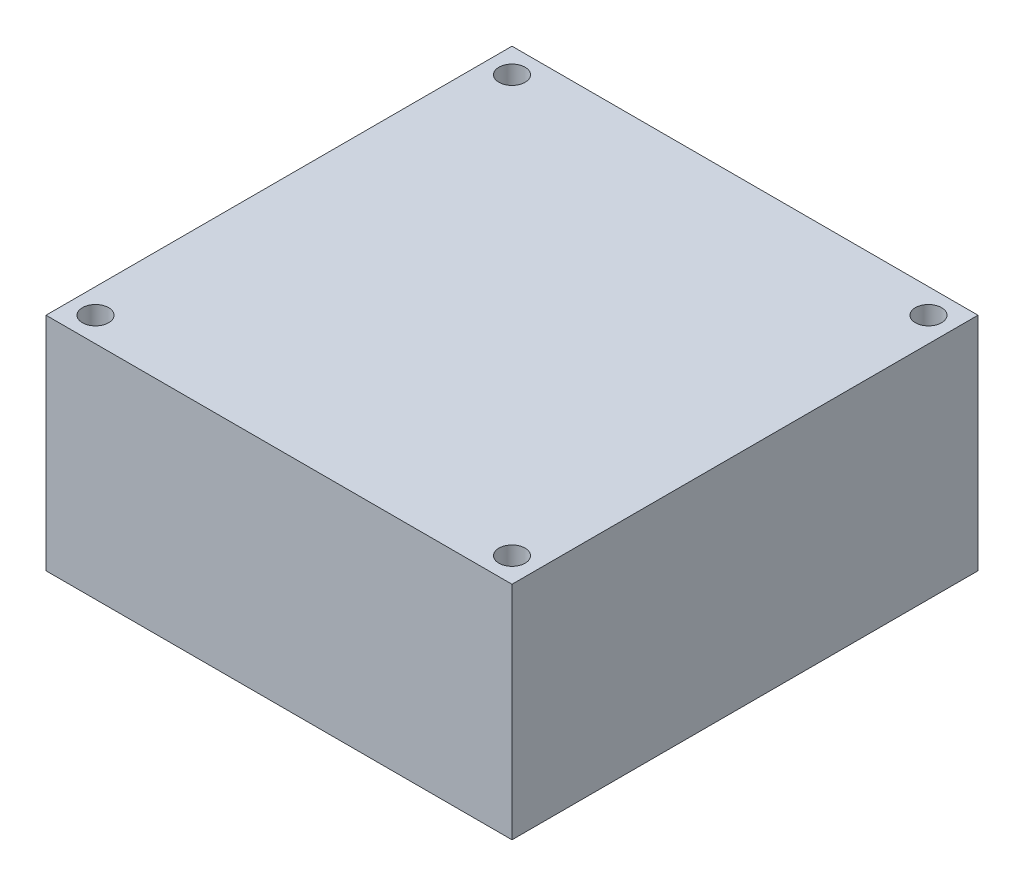
SolidWorks part; units mm, degrees
material "ABS"
ref_plane "Front Plane" through (0, 0, 0) normal (0, 0, 1) x (1, 0, 0)
ref_plane "Top Plane" through (0, 0, 0) normal (0, 1, 0) x (1, 0, 0)
ref_plane "Right Plane" through (0, 0, 0) normal (1, 0, 0) x (0, 0, -1)
sketch "Sketch1" plane through (0, 0, 0) normal (0, 1, 0) x (1, 0, 0)
  line L1 (0, 0) -> (80, 0)
  line L2 (0, 0) -> (0, 80)
  line L3 (0, 80) -> (80, 80)
  line L4 (80, 0) -> (80, 80)
  dimension "D1" = 80
  dimension "D2" = 80
extrude "Boss-Extrude1" add sketch "Sketch1" along normal blind 38
sketch "Sketch2" plane through (0, 38, 0) normal (0, 1, 0) x (1, 0, 0)
  line L1 (80, 80) -> (0, 80) construction
  line L2 (0, 80) -> (0, 0) construction
  circle A0 centre (4.25, 75.75) radius 2.25
  circle A1 centre (75.75, 75.75) radius 2.25
  circle A2 centre (75.75, 4.25) radius 2.25
  circle A3 centre (4.25, 4.25) radius 2.25
  dimension "D1" = 4.5
  dimension "D2" = 71.5
  dimension "D3" = 71.5
  dimension "D4" = 4.25
  dimension "D5" = 4.25
extrude "Cut-Extrude1" cut sketch "Sketch2" against normal through all
